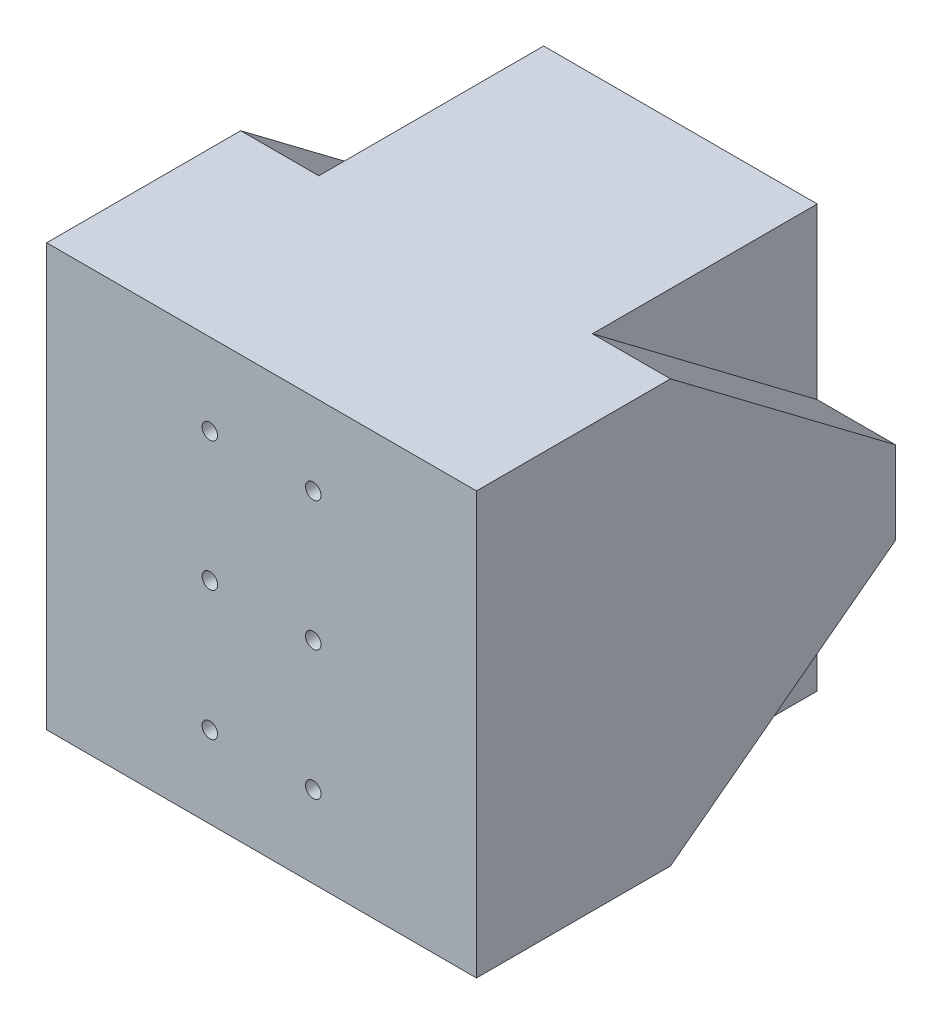
SolidWorks part; units mm, degrees
ref_plane "前视基准面" through (0, 0, 0) normal (0, 0, 1) x (1, 0, 0)
ref_plane "上视基准面" through (0, 0, 0) normal (0, 1, 0) x (1, 0, 0)
ref_plane "右视基准面" through (0, 0, 0) normal (1, 0, 0) x (0, 0, -1)
sketch "草图1" plane through (0, 0, 0) normal (0, 0, 1) x (1, 0, 0)
  line L1 (-26.45, -40.78) -> (26.45, -40.78)
  line L2 (-26.45, -40.78) -> (-26.45, 40.78)
  line L3 (-26.45, 40.78) -> (26.45, 40.78)
  line L4 (26.45, -40.78) -> (26.45, 40.78)
  line L5 (-26.45, -40.78) -> (26.45, 40.78) construction
  line L6 (-26.45, 40.78) -> (26.45, -40.78) construction
  point P0 (0, 0)
  dimension "D1" = 52.9
  dimension "D2" = 81.56
extrude "凸台-拉伸1" add sketch "草图1" along normal blind 80.99
sketch "草图2" plane through (0, 0, 0) normal (0, 0, -1) x (-1, 0, 0)
  line L0 (-26.45, 40.78) -> (26.45, 40.78) construction
  line L1 (-16.45, -30.78) -> (16.45, -30.78)
  line L2 (-16.45, -30.78) -> (-16.45, 30.78)
  line L3 (-16.45, 30.78) -> (16.45, 30.78)
  line L4 (16.45, -30.78) -> (16.45, 30.78)
  line L5 (-16.45, -30.78) -> (16.45, 30.78) construction
  line L6 (-16.45, 30.78) -> (16.45, -30.78) construction
  line L7 (26.45, 40.78) -> (26.45, -40.78) construction
  point P0 (0, 0)
  dimension "D1" = 10
  dimension "D2" = 10
extrude "切除-拉伸1" cut sketch "草图2" against normal blind 75.99
sketch "草图3" plane through (-26.45, 0, 0) normal (-1, 0, 0) x (0, 0, 1)
  line L0 (80.99, 40.78) -> (43.47, 40.78)
  line L2 (43.47, 40.78) -> (0, 8.02)
  line L3 (0, 40.78) -> (0, -40.78) construction
  line L4 (0, 8.02) -> (0, -8.02)
  line L5 (0, -8.02) -> (43.47, -40.78)
  line L6 (80.99, -40.78) -> (0, -40.78) construction
  line L7 (43.47, -40.78) -> (80.99, -40.78)
  line L8 (80.99, -40.78) -> (80.99, 40.78)
  point P3 (0, 0)
  dimension "D1" = 37.52
  dimension "D2" = 37.52
  dimension "D3" = 16.04
extrude "凸台-拉伸2" add sketch "草图3" along normal blind 15.1
mirror "镜向1" about plane through (0, 0, 0) normal (1, 0, 0) of "凸台-拉伸2"
sketch "草图4" plane through (0, 0, 80.99) normal (0, 0, 1) x (1, 0, 0)
  line L1 (-10, -25) -> (10, -25) construction
  line L2 (-10, -25) -> (-10, 25) construction
  line L3 (-10, 25) -> (10, 25) construction
  line L4 (10, -25) -> (10, 25) construction
  line L5 (-10, -25) -> (10, 25) construction
  line L6 (-10, 25) -> (10, -25) construction
  circle A0 centre (-10, 25) radius 1.5
  circle A2 centre (10, 25) radius 1.5
  circle A3 centre (-10, -25) radius 1.5
  circle A5 centre (10, -25) radius 1.5
  circle A6 centre (-10, 0) radius 1.5
  circle A7 centre (10, 0) radius 1.5
  point P0 (0, 0)
  dimension "D3" = 3
  dimension "D4" = 3
  dimension "D5" = 3
  dimension "D6" = 3
  dimension "D7" = 3
  dimension "D8" = 3
  dimension "D1" = 20
  dimension "D2" = 50
extrude "切除-拉伸2" cut sketch "草图4" against normal through all
